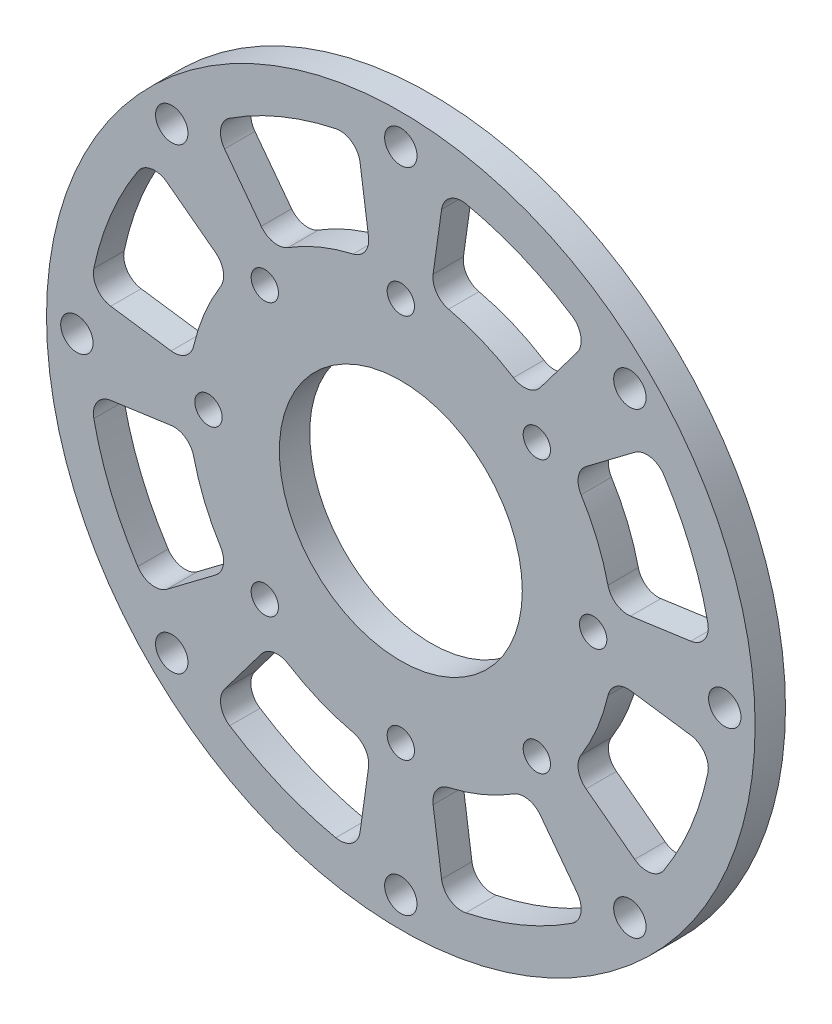
SolidWorks part; units mm, degrees
material "Thornel Mat VMA"
ref_plane "前视基准面" through (0, 0, 0) normal (0, 0, 1) x (1, 0, 0)
ref_plane "上视基准面" through (0, 0, 0) normal (0, 1, 0) x (1, 0, 0)
ref_plane "右视基准面" through (0, 0, 0) normal (1, 0, 0) x (0, 0, -1)
sketch "草图1" plane through (0, 0, 0) normal (0, 0, 1) x (1, 0, 0)
  line L0 (0, 0) -> (0, 32) construction
  line L1 (0, 0) -> (-22.6274, 22.6274) construction
  circle A0 centre (0, 0) radius 35
  circle A1 centre (0, 0) radius 32 construction
  circle A2 centre (0, 0) radius 19 construction
  circle A3 centre (-22.6274, 22.6274) radius 1.6
  circle A4 centre (0, 32) radius 1.6
  circle A5 centre (22.6274, 22.6274) radius 1.6
  circle A6 centre (32, 0) radius 1.6
  circle A7 centre (22.6274, -22.6274) radius 1.6
  circle A8 centre (0, -32) radius 1.6
  circle A9 centre (-22.6274, -22.6274) radius 1.6
  circle A10 centre (-32, 0) radius 1.6
  circle A11 centre (-13.435, 13.435) radius 1.35
  circle A12 centre (0, 19) radius 1.35
  circle A13 centre (13.435, 13.435) radius 1.35
  circle A14 centre (19, 0) radius 1.35
  circle A15 centre (13.435, -13.435) radius 1.35
  circle A16 centre (0, -19) radius 1.35
  circle A17 centre (-13.435, -13.435) radius 1.35
  circle A18 centre (-19, 0) radius 1.35
  circle A19 centre (0, 0) radius 12
  point P25 (0, 0)
  point P42 (0, 0)
  dimension "D1" = 70
  dimension "D2" = 64
  dimension "D3" = 38
  dimension "D5" = 3.2
  dimension "D7" = 2.7
  dimension "D9" = 24
  dimension "D4" = 45
  dimension "D6" = 8
  dimension "D8" = 8
extrude "凸台-拉伸1" add sketch "草图1" along normal blind 3
sketch "草图2" plane through (0, 0, 3) normal (0, 0, 1) x (1, 0, 0)
  line L0 (0, 0) -> (0, 32) construction
  line L1 (0, 0) -> (22.6274, 22.6274) construction
  line L2 (4.3144, 30.6983) -> (0, 0) construction
  line L3 (0, 0) -> (18.6563, 24.7577) construction
  line L4 (4.0264, 28.6494) -> (3.1889, 22.6899)
  line L5 (13.7893, 18.299) -> (17.4111, 23.1053)
  line L20 (23.1053, 17.4111) -> (18.299, 13.7893)
  line L21 (22.6899, 3.1889) -> (28.6494, 4.0264)
  line L22 (28.6494, -4.0264) -> (22.6899, -3.1889)
  line L23 (18.299, -13.7893) -> (23.1053, -17.4111)
  line L24 (17.4111, -23.1053) -> (13.7893, -18.299)
  line L25 (3.1889, -22.6899) -> (4.0264, -28.6494)
  line L26 (-4.0264, -28.6494) -> (-3.1889, -22.6899)
  line L27 (-13.7893, -18.299) -> (-17.4111, -23.1053)
  line L28 (-23.1053, -17.4111) -> (-18.299, -13.7893)
  line L29 (-22.6899, -3.1889) -> (-28.6494, -4.0264)
  line L30 (-28.6494, 4.0264) -> (-22.6899, 3.1889)
  line L31 (-18.299, 13.7893) -> (-23.1053, 17.4111)
  line L32 (-17.4111, 23.1053) -> (-13.7893, 18.299)
  line L33 (-3.1889, 22.6899) -> (-4.0264, 28.6494)
  arc A0 (11.1319, 17.8068) -> (4.7199, 20.4627) centre (0, 0) ccw
  arc A1 (16.9044, 25.9854) -> (6.4212, 30.3277) centre (0, 0) ccw
  arc A16 (4.0264, 28.6494) -> (6.4212, 30.3277) centre (6.0069, 28.3711) cw
  arc A17 (17.4111, 23.1053) -> (16.9044, 25.9854) centre (15.8138, 24.3089) ccw
  arc A18 (11.1319, 17.8068) -> (13.7893, 18.299) centre (12.192, 19.5027) ccw
  arc A19 (4.7199, 20.4627) -> (3.1889, 22.6899) centre (5.1694, 22.4115) cw
  arc A20 (20.4627, 4.7199) -> (17.8068, 11.1319) centre (0, 0) ccw
  arc A21 (30.3277, 6.4212) -> (25.9854, 16.9044) centre (0, 0) ccw
  arc A22 (23.1053, 17.4111) -> (25.9854, 16.9044) centre (24.3089, 15.8138) cw
  arc A23 (28.6494, 4.0264) -> (30.3277, 6.4212) centre (28.3711, 6.0069) ccw
  arc A24 (20.4627, 4.7199) -> (22.6899, 3.1889) centre (22.4115, 5.1694) ccw
  arc A25 (17.8068, 11.1319) -> (18.299, 13.7893) centre (19.5027, 12.192) cw
  arc A26 (17.8068, -11.1319) -> (20.4627, -4.7199) centre (0, 0) ccw
  arc A27 (25.9854, -16.9044) -> (30.3277, -6.4212) centre (0, 0) ccw
  arc A28 (28.6494, -4.0264) -> (30.3277, -6.4212) centre (28.3711, -6.0069) cw
  arc A29 (23.1053, -17.4111) -> (25.9854, -16.9044) centre (24.3089, -15.8138) ccw
  arc A30 (17.8068, -11.1319) -> (18.299, -13.7893) centre (19.5027, -12.192) ccw
  arc A31 (20.4627, -4.7199) -> (22.6899, -3.1889) centre (22.4115, -5.1694) cw
  arc A32 (4.7199, -20.4627) -> (11.1319, -17.8068) centre (0, 0) ccw
  arc A33 (6.4212, -30.3277) -> (16.9044, -25.9854) centre (0, 0) ccw
  arc A34 (17.4111, -23.1053) -> (16.9044, -25.9854) centre (15.8138, -24.3089) cw
  arc A35 (4.0264, -28.6494) -> (6.4212, -30.3277) centre (6.0069, -28.3711) ccw
  arc A36 (4.7199, -20.4627) -> (3.1889, -22.6899) centre (5.1694, -22.4115) ccw
  arc A37 (11.1319, -17.8068) -> (13.7893, -18.299) centre (12.192, -19.5027) cw
  arc A38 (-11.1319, -17.8068) -> (-4.7199, -20.4627) centre (0, 0) ccw
  arc A39 (-16.9044, -25.9854) -> (-6.4212, -30.3277) centre (0, 0) ccw
  arc A40 (-4.0264, -28.6494) -> (-6.4212, -30.3277) centre (-6.0069, -28.3711) cw
  arc A41 (-17.4111, -23.1053) -> (-16.9044, -25.9854) centre (-15.8138, -24.3089) ccw
  arc A42 (-11.1319, -17.8068) -> (-13.7893, -18.299) centre (-12.192, -19.5027) ccw
  arc A43 (-4.7199, -20.4627) -> (-3.1889, -22.6899) centre (-5.1694, -22.4115) cw
  arc A44 (-20.4627, -4.7199) -> (-17.8068, -11.1319) centre (0, 0) ccw
  arc A45 (-30.3277, -6.4212) -> (-25.9854, -16.9044) centre (0, 0) ccw
  arc A46 (-23.1053, -17.4111) -> (-25.9854, -16.9044) centre (-24.3089, -15.8138) cw
  arc A47 (-28.6494, -4.0264) -> (-30.3277, -6.4212) centre (-28.3711, -6.0069) ccw
  arc A48 (-20.4627, -4.7199) -> (-22.6899, -3.1889) centre (-22.4115, -5.1694) ccw
  arc A49 (-17.8068, -11.1319) -> (-18.299, -13.7893) centre (-19.5027, -12.192) cw
  arc A50 (-17.8068, 11.1319) -> (-20.4627, 4.7199) centre (0, 0) ccw
  arc A51 (-25.9854, 16.9044) -> (-30.3277, 6.4212) centre (0, 0) ccw
  arc A52 (-28.6494, 4.0264) -> (-30.3277, 6.4212) centre (-28.3711, 6.0069) cw
  arc A53 (-23.1053, 17.4111) -> (-25.9854, 16.9044) centre (-24.3089, 15.8138) ccw
  arc A54 (-17.8068, 11.1319) -> (-18.299, 13.7893) centre (-19.5027, 12.192) ccw
  arc A55 (-20.4627, 4.7199) -> (-22.6899, 3.1889) centre (-22.4115, 5.1694) cw
  arc A56 (-4.7199, 20.4627) -> (-11.1319, 17.8068) centre (0, 0) ccw
  arc A57 (-6.4212, 30.3277) -> (-16.9044, 25.9854) centre (0, 0) ccw
  arc A58 (-17.4111, 23.1053) -> (-16.9044, 25.9854) centre (-15.8138, 24.3089) cw
  arc A59 (-4.0264, 28.6494) -> (-6.4212, 30.3277) centre (-6.0069, 28.3711) ccw
  arc A60 (-4.7199, 20.4627) -> (-3.1889, 22.6899) centre (-5.1694, 22.4115) ccw
  arc A61 (-11.1319, 17.8068) -> (-13.7893, 18.299) centre (-12.192, 19.5027) cw
  point P18 (12.6381, 16.7713)
  point P21 (2.9226, 20.7956)
  point P41 (0, 0)
  point P110 (0, 0)
  dimension "D1" = 42
  dimension "D2" = 62
  dimension "D5" = 2
  dimension "D3" = 8
  dimension "D4" = 8
  dimension "D6" = 8
extrude "切除-拉伸1" cut sketch "草图2" against normal blind 3
